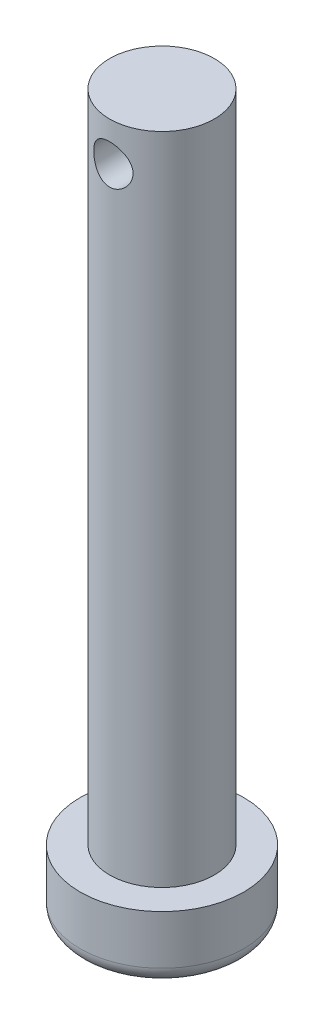
SolidWorks part; units mm, degrees
ref_plane "Front Plane" through (0, 0, 0) normal (0, 0, 1) x (1, 0, 0)
ref_plane "Top Plane" through (0, 0, 0) normal (0, 1, 0) x (1, 0, 0)
ref_plane "Right Plane" through (0, 0, 0) normal (1, 0, 0) x (0, 0, -1)
sketch "Sketch1" plane through (0, 0, 0) normal (0, 1, 0) x (1, 0, 0)
  circle A0 centre (0, 0) radius 12.5
  dimension "D1" = 25
extrude "Boss-Extrude1" add sketch "Sketch1" along normal blind 10
fillet "Fillet1" radius 2.5 1 edges at (0, 0, 12.5)
sketch "Sketch2" plane through (0, 10, 0) normal (0, 1, 0) x (1, 0, 0)
  circle A0 centre (0, 0) radius 8
  dimension "D1" = 16
extrude "Boss-Extrude2" add sketch "Sketch2" along normal blind 100
sketch "Sketch3" plane through (0, 0, 0) normal (0, 0, 1) x (1, 0, 0)
  line L0 (8, 110) -> (-8, 110) construction
  circle A0 centre (0, 104) radius 3
  point P4 (0, 0)
  dimension "D1" = 6
  dimension "D2" = 6
extrude "Cut-Extrude1" cut sketch "Sketch3" against normal mid plane 100
